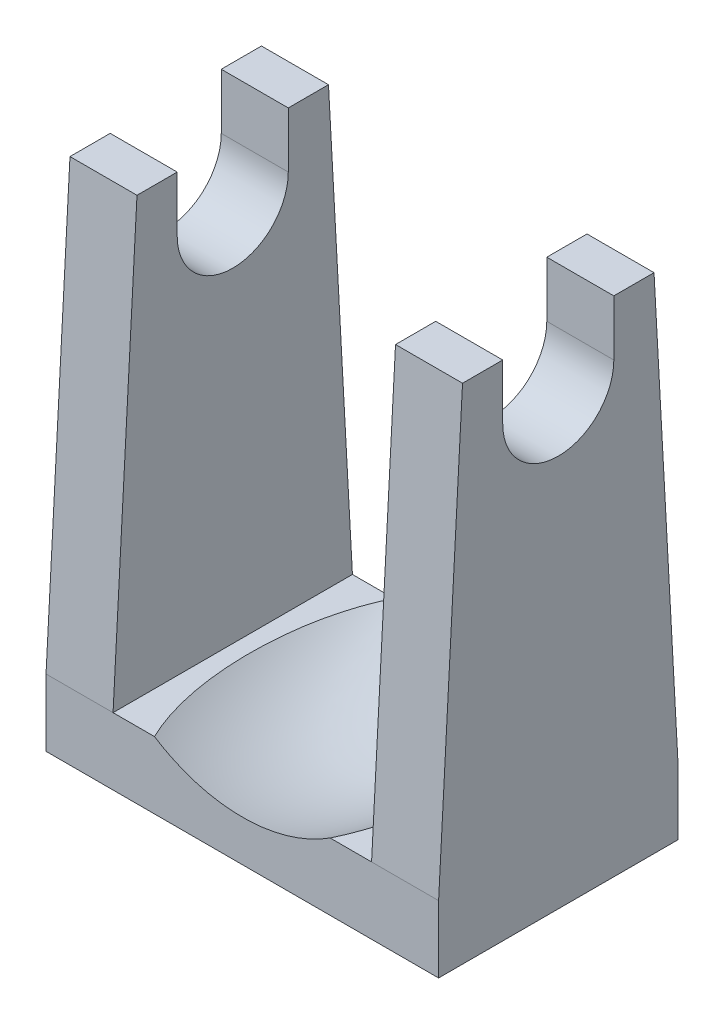
SolidWorks part; units mm, degrees
ref_plane "Front Plane" through (0, 0, 0) normal (0, 0, 1) x (1, 0, 0)
ref_plane "Top Plane" through (0, 0, 0) normal (0, 1, 0) x (1, 0, 0)
ref_plane "Right Plane" through (0, 0, 0) normal (1, 0, 0) x (0, 0, -1)
sketch "Sketch1" plane through (0, 0, 0) normal (0, 0, 1) x (1, 0, 0)
  line L0 (5.207, 0) -> (-5.207, 0)
  line L1 (-5.207, 0) -> (-5.207, 13.3472)
  line L2 (-5.207, 13.3472) -> (-3.429, 13.3472)
  line L3 (-3.429, 13.3472) -> (-3.429, 1.778)
  line L4 (-3.429, 1.778) -> (3.429, 1.778)
  line L5 (0, 1.778) -> (0, 0) construction
  line L6 (0, 0) -> (0, -4.2091) construction
  line L7 (3.429, 13.3472) -> (3.429, 1.778)
  line L8 (5.207, 13.3472) -> (3.429, 13.3472)
  line L9 (5.207, 0) -> (5.207, 13.3472)
  line L10 (0, 1.778) -> (0, 11.874) construction
  point P13 (-5.207, 14.9037)
  dimension "D1" = 1.778
  dimension "D2" = 6.858
  dimension "D3" = 1.778
  dimension "D4" = 1.4732
  dimension "D5" = 11.874
extrude "Boss-Extrude1" add sketch "Sketch1" along normal mid plane 6.35
sketch "Sketch2" plane through (0, 0, 0) normal (1, 0, 0) x (0, 0, -1)
  line L0 (0, 13.3472) -> (0, 11.874) construction
  line L1 (-3.175, 13.3472) -> (3.175, 13.3472) construction
  line L2 (1.4732, 13.3472) -> (1.4732, 11.874)
  line L3 (-1.4732, 13.3472) -> (-1.4732, 11.874)
  arc A0 (1.4732, 13.3472) -> (-1.4732, 13.3472) centre (0, 13.3472) ccw
  arc A1 (-1.4732, 11.874) -> (1.4732, 11.874) centre (0, 11.874) ccw
  point P5 (0, 12.6106)
  dimension "D1" = 2.9464
  dimension "D2" = 1.4732
extrude "Cut-Extrude1" cut sketch "Sketch2" against normal through all both and the other way through all
sketch "Sketch4" plane through (0, 0, 0) normal (1, 0, 0) x (0, 0, -1)
  line L0 (-3.175, 1.778) -> (-3.175, 13.3472) construction
  line L2 (-3.175, 1.778) -> (-3.175, 13.3472)
  line L4 (-3.175, 1.778) -> (-2.54, 13.3472)
  line L6 (-3.175, 13.3472) -> (-1.4732, 13.3472) construction
  line L7 (-3.175, 13.3472) -> (-2.54, 13.3472)
  point P2 (-2.3241, 13.3472)
  dimension "D1" = 1.0668
extrude "Cut-Extrude2" cut sketch "Sketch4" against normal through all both and the other way through all
mirror "Mirror1" about plane through (0, 0, 0) normal (0, 0, 1) of "Cut-Extrude2"
sketch "Sketch3" plane through (0, 0, 0) normal (0, 0, 1) x (1, 0, 0)
  line L0 (3.429, 1.778) -> (-3.429, 1.778) construction
  line L1 (-2.7907, 1.778) -> (2.7907, 1.778) construction
  line L2 (0, 11.874) -> (6.2441, 11.874) construction
  line L3 (-3.12, 1.905) -> (3.12, 1.905)
  line L4 (0, 1.778) -> (0, 11.874) construction
  arc A4 (-3.12, 1.905) -> (3.12, 1.905) centre (0, 5.1007) ccw
  arc A6 (-2.7907, 1.778) -> (2.7907, 1.778) centre (0, 5.1007) ccw construction
  dimension "D2" = 4.3392
  dimension "D3" = 5.5815
  dimension "D1" = 0.127
revolve "Cut-Revolve1" cut sketch "Sketch3" angle 360 about L2
